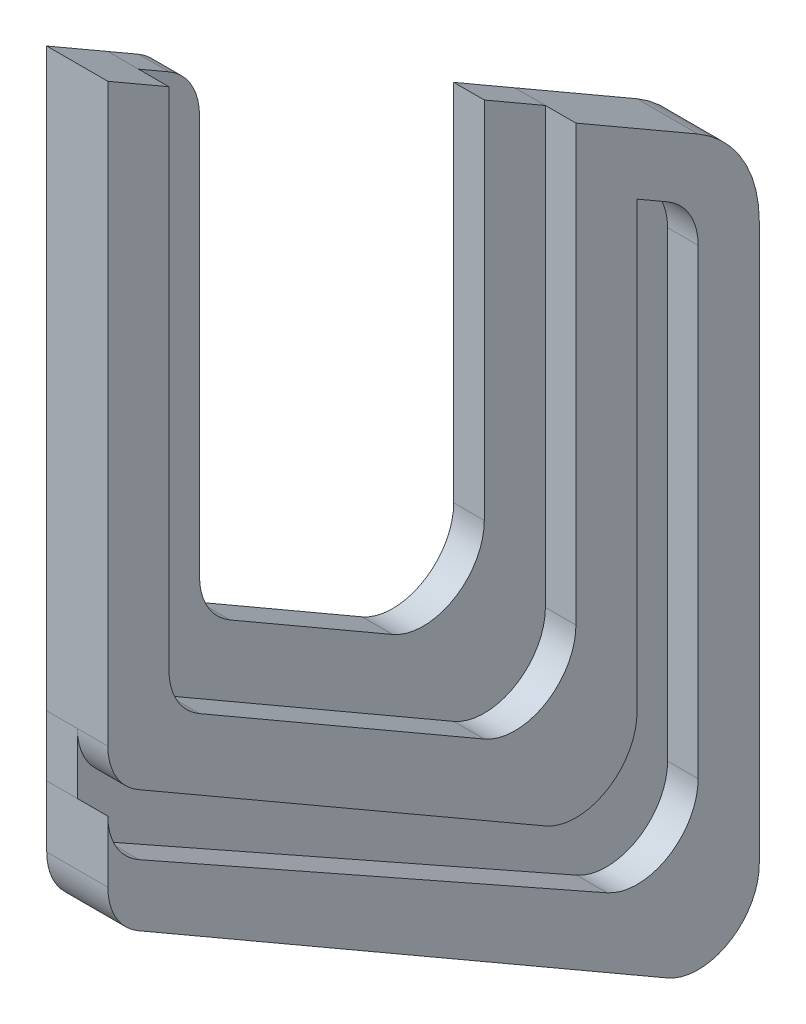
SolidWorks part; units mm, degrees
ref_plane "Plan de face" through (0, 0, 0) normal (1, 0, 0) x (0, 1, 0)
ref_plane "Plan de dessus" through (0, 0, 0) normal (0, 0, 1) x (0, 1, 0)
ref_plane "Plan de droite" through (0, 0, 0) normal (0, 1, 0) x (-1, 0, 0)
sketch "Sketch1" plane through (0, 0, 0) normal (1, 0, 0) x (0, 1, 0)
  line L0 (94.9825, 86.6025) -> (0.756, 86.6025)
  line L1 (-7.9042, 81.6025) -> (-46.3572, 15)
  line L2 (-37.697, 0) -> (34.9825, 0)
  line L3 (83.4355, 76.6025) -> (6.5295, 76.6025)
  line L4 (-2.1307, 71.6025) -> (-29.0367, 25)
  line L5 (-20.3765, 10) -> (50.756, 10)
  line L6 (94.9825, 86.6025) -> (92.0958, 81.6025)
  line L7 (-37.697, 10) -> (44.9825, 10) construction
  line L8 (50.756, 10) -> (44.9825, 0)
  line L9 (94.9825, 76.6025) -> (0.756, 76.6025) construction
  line L10 (0.756, 76.6025) -> (-37.697, 10) construction
  line L11 (50.756, 10) -> (39.209, -10)
  line L12 (-5.0175, 86.6025) -> (-9.1631, 86.6025) construction
  line L13 (-15.0175, 86.6025) -> (-19.244, 86.6025)
  line L14 (-27.9042, 81.6025) -> (-77.9042, -5)
  line L15 (-69.244, -20) -> (21.8885, -20)
  line L16 (23.4355, -10) -> (-52.1628, -10)
  line L17 (-60.8829, 4.8949) -> (-17.8831, 81.4974)
  line L18 (34.9825, 0) -> (32.0958, -5)
  line L19 (-37.697, 0) -> (44.9825, 0) construction
  line L20 (-15.0175, 86.6025) -> (-9.1631, 86.6025)
  line L21 (83.4355, 76.6025) -> (89.209, 76.6025)
  line L22 (89.209, 76.6025) -> (92.0958, 81.6025)
  arc A0 (-37.697, 0) -> (-46.3572, 15) centre (-37.697, 10) cw
  arc A1 (0.756, 86.6025) -> (-7.9042, 81.6025) centre (0.756, 76.6025) ccw
  arc A5 (-20.3765, 10) -> (-29.0367, 25) centre (-20.3765, 20) cw
  arc A6 (-37.697, 10) -> (-37.697, 10) centre (-37.697, 10) cw construction
  arc A7 (-2.1307, 71.6025) -> (6.5295, 76.6025) centre (6.5295, 66.6025) cw
  arc A8 (0.756, 76.6025) -> (0.756, 76.6025) centre (0.756, 76.6025) ccw construction
  arc A9 (-69.244, -20) -> (-77.9042, -5) centre (-69.244, -10) cw
  arc A10 (32.0958, -5) -> (23.4355, -10) centre (23.4355, 0) cw
  arc A11 (39.209, -10) -> (21.8885, -20) centre (21.8885, 0) cw
  arc A12 (-60.8829, 4.8949) -> (-52.1628, -10) centre (-52.1628, 0) ccw
  arc A13 (-27.9042, 81.6025) -> (-19.244, 86.6025) centre (-19.244, 76.6025) cw
  arc A14 (-17.8831, 81.4974) -> (-9.1631, 86.6025) centre (-9.1631, 76.6025) cw
  point P7 (-55.0175, 0)
  point P10 (-5.0175, 86.6025)
  point P44 (33.4355, -20)
  point P50 (-25.0175, 86.6025)
  dimension "D5" = 10
  dimension "D8" = 10
  dimension "D11" = 10
  dimension "D12" = 10
  dimension "D13" = 20
  dimension "D14" = 10
  dimension "D15" = 10
  dimension "D16" = 10
  dimension "D1" = 100
  dimension "D2" = 60
  dimension "D3" = 100
  dimension "D4" = 100
  dimension "D9" = 10
  dimension "D10" = 10
  dimension "10" = 20
  dimension "D6" = 10
extrude "Boss-Extrude1" add sketch "Sketch1" along normal blind 10 contours L11 A11 L15 A9 L14 A13 L13 L20 A14 L17 A12 L16 A10 L18 L2 A0 L1 A1 L0 L6 L22 L21 L3 A7 L4 A5 L5
sketch "Sketch2" plane through (10, 0, 0) normal (1, 0, 0) x (0, 1, 0)
  line L0 (-9.1631, 86.6025) -> (0.756, 86.6025)
  line L14 (-9.1631, 86.6025) -> (-19.244, 86.6025)
  line L15 (-27.9042, 81.6025) -> (-77.9042, -5)
  line L16 (-69.244, -20) -> (21.8885, -20)
  line L17 (39.209, -10) -> (50.756, 10)
  line L18 (50.756, 10) -> (-20.3765, 10)
  line L19 (-29.0367, 25) -> (-2.1307, 71.6025)
  line L20 (6.5295, 76.6025) -> (89.209, 76.6025)
  line L21 (89.209, 76.6025) -> (94.9825, 86.6025)
  line L22 (94.9825, 86.6025) -> (0.756, 86.6025)
  line L23 (-7.9042, 81.6025) -> (-46.3572, 15)
  line L24 (-37.697, 0) -> (34.9825, 0)
  line L25 (34.9825, 0) -> (32.0958, -5)
  line L26 (23.4355, -10) -> (-52.1628, -10)
  line L27 (-60.8829, 4.8949) -> (-17.8831, 81.4974)
  line L28 (-9.1631, 86.6025) -> (-19.244, 86.6025)
  line L29 (-27.9042, 81.6025) -> (-77.9042, -5)
  line L30 (-69.244, -20) -> (21.8885, -20)
  line L31 (39.209, -10) -> (50.756, 10)
  line L32 (50.756, 10) -> (-20.3765, 10)
  line L33 (-29.0367, 25) -> (-2.1307, 71.6025)
  line L34 (6.5295, 76.6025) -> (89.209, 76.6025)
  line L35 (89.209, 76.6025) -> (94.9825, 86.6025)
  line L36 (94.9825, 86.6025) -> (0.756, 86.6025)
  line L37 (-7.9042, 81.6025) -> (-46.3572, 15)
  line L38 (-37.697, 0) -> (34.9825, 0)
  line L39 (34.9825, 0) -> (32.0958, -5)
  line L40 (23.4355, -10) -> (-52.1628, -10)
  line L41 (-60.8829, 4.8949) -> (-17.8831, 81.4974)
  arc A12 (-9.1631, 86.6025) -> (-17.8831, 81.4974) centre (-9.1631, 76.6025) ccw
  arc A14 (-19.244, 86.6025) -> (-27.9042, 81.6025) centre (-19.244, 76.6025) ccw
  arc A15 (-77.9042, -5) -> (-69.244, -20) centre (-69.244, -10) ccw
  arc A16 (21.8885, -20) -> (39.209, -10) centre (21.8885, 0) ccw
  arc A17 (-29.0367, 25) -> (-20.3765, 10) centre (-20.3765, 20) ccw
  arc A18 (6.5295, 76.6025) -> (-2.1307, 71.6025) centre (6.5295, 66.6025) ccw
  arc A20 (0.756, 86.6025) -> (-7.9042, 81.6025) centre (0.756, 76.6025) ccw
  arc A21 (-46.3572, 15) -> (-37.697, 0) centre (-37.697, 10) ccw
  arc A22 (23.4355, -10) -> (32.0958, -5) centre (23.4355, 0) ccw
  arc A23 (-60.8829, 4.8949) -> (-52.1628, -10) centre (-52.1628, 0) ccw
  arc A24 (-9.1631, 86.6025) -> (-17.8831, 81.4974) centre (-9.1631, 76.6025) ccw
  arc A26 (-19.244, 86.6025) -> (-27.9042, 81.6025) centre (-19.244, 76.6025) ccw
  arc A27 (-77.9042, -5) -> (-69.244, -20) centre (-69.244, -10) ccw
  arc A28 (21.8885, -20) -> (39.209, -10) centre (21.8885, 0) ccw
  arc A29 (-29.0367, 25) -> (-20.3765, 10) centre (-20.3765, 20) ccw
  arc A30 (6.5295, 76.6025) -> (-2.1307, 71.6025) centre (6.5295, 66.6025) ccw
  arc A32 (0.756, 86.6025) -> (-7.9042, 81.6025) centre (0.756, 76.6025) ccw
  arc A33 (-46.3572, 15) -> (-37.697, 0) centre (-37.697, 10) ccw
  arc A34 (23.4355, -10) -> (32.0958, -5) centre (23.4355, 0) ccw
  arc A35 (-60.8829, 4.8949) -> (-52.1628, -10) centre (-52.1628, 0) ccw
  arc M27 (-17.8831, 81.4974) -> (-9.1631, 86.6025) centre (-9.1631, 76.6025) cw
  arc M44 (0.756, 86.6025) -> (-7.9042, 81.6025) centre (0.756, 76.6025) ccw
  line M45 (-7.9042, 81.6025) -> (-46.3572, 15)
  arc M46 (-46.3572, 15) -> (-37.697, 0) centre (-37.697, 10) ccw
  line M47 (-37.697, 0) -> (34.9825, 0)
  line M48 (34.9825, 0) -> (32.0958, -5)
  arc M49 (32.0958, -5) -> (23.4355, -10) centre (23.4355, 0) cw
  line M50 (23.4355, -10) -> (-52.1628, -10)
  arc M51 (-52.1628, -10) -> (-60.8829, 4.8949) centre (-52.1628, 0) cw
  line M52 (-60.8829, 4.8949) -> (-17.8831, 81.4974)
  dimension "D1" = 0
extrude "Boss-Extrude2" add sketch "Sketch2" against normal blind 5 from offset 5 separate body contours L0 M27 M52 M51 M50 M49 M48 M47 M46 M45 M44 offset against normal yes
sketch "Sketch3" plane through (5, 0, 0) normal (1, 0, 0) x (0, 1, 0)
  line L14 (50.756, 10) -> (-20.3765, 10)
  line L15 (-29.0367, 25) -> (-2.1307, 71.6025)
  line L16 (6.5295, 76.6025) -> (89.209, 76.6025)
  line L17 (89.209, 76.6025) -> (94.9825, 86.6025)
  line L18 (94.9825, 86.6025) -> (0.756, 86.6025)
  line L19 (-7.9042, 81.6025) -> (-46.3572, 15)
  line L20 (-37.697, 0) -> (34.9825, 0)
  line L21 (34.9825, 0) -> (32.0958, -5)
  line L22 (23.4355, -10) -> (-52.1628, -10)
  line L23 (-60.8829, 4.8949) -> (-17.8831, 81.4974)
  line L24 (-9.1631, 86.6025) -> (-19.244, 86.6025)
  line L25 (-27.9042, 81.6025) -> (-77.9042, -5)
  line L26 (-69.244, -20) -> (21.8885, -20)
  line L27 (39.209, -10) -> (50.756, 10)
  line L28 (50.756, 10) -> (-20.3765, 10)
  line L29 (-29.0367, 25) -> (-2.1307, 71.6025)
  line L30 (6.5295, 76.6025) -> (89.209, 76.6025)
  line L31 (89.209, 76.6025) -> (94.9825, 86.6025)
  line L32 (94.9825, 86.6025) -> (0.756, 86.6025)
  line L33 (-7.9042, 81.6025) -> (-46.3572, 15)
  line L34 (-37.697, 0) -> (34.9825, 0)
  line L35 (34.9825, 0) -> (32.0958, -5)
  line L36 (23.4355, -10) -> (-52.1628, -10)
  line L37 (-60.8829, 4.8949) -> (-17.8831, 81.4974)
  line L38 (-9.1631, 86.6025) -> (-19.244, 86.6025)
  line L39 (-27.9042, 81.6025) -> (-77.9042, -5)
  line L40 (-69.244, -20) -> (21.8885, -20)
  line L41 (39.209, -10) -> (50.756, 10)
  line L42 (-11.7162, 35) -> (3.6428, 61.6025)
  line L43 (12.303, 66.6025) -> (77.662, 66.6025)
  line L44 (56.5295, 20) -> (-3.0559, 20)
  line L45 (89.209, 76.6025) -> (86.3223, 71.6025)
  line L46 (50.756, 20) -> (-20.3765, 20) construction
  line L47 (6.5295, 66.6025) -> (89.209, 66.6025) construction
  line L48 (56.5295, 20) -> (50.756, 10)
  line L49 (-20.3765, 20) -> (6.5295, 66.6025) construction
  arc A10 (-29.0367, 25) -> (-20.3765, 10) centre (-20.3765, 20) ccw
  arc A11 (6.5295, 76.6025) -> (-2.1307, 71.6025) centre (6.5295, 66.6025) ccw
  arc A12 (0.756, 86.6025) -> (-7.9042, 81.6025) centre (0.756, 76.6025) ccw
  arc A13 (-46.3572, 15) -> (-37.697, 0) centre (-37.697, 10) ccw
  arc A14 (23.4355, -10) -> (32.0958, -5) centre (23.4355, 0) ccw
  arc A15 (-60.8829, 4.8949) -> (-52.1628, -10) centre (-52.1628, 0) ccw
  arc A16 (-9.1631, 86.6025) -> (-17.8831, 81.4974) centre (-9.1631, 76.6025) ccw
  arc A17 (-19.244, 86.6025) -> (-27.9042, 81.6025) centre (-19.244, 76.6025) ccw
  arc A18 (-77.9042, -5) -> (-69.244, -20) centre (-69.244, -10) ccw
  arc A19 (21.8885, -20) -> (39.209, -10) centre (21.8885, 0) ccw
  arc A20 (-29.0367, 25) -> (-20.3765, 10) centre (-20.3765, 20) ccw
  arc A21 (6.5295, 76.6025) -> (-2.1307, 71.6025) centre (6.5295, 66.6025) ccw
  arc A22 (0.756, 86.6025) -> (-7.9042, 81.6025) centre (0.756, 76.6025) ccw
  arc A23 (-46.3572, 15) -> (-37.697, 0) centre (-37.697, 10) ccw
  arc A24 (23.4355, -10) -> (32.0958, -5) centre (23.4355, 0) ccw
  arc A25 (-60.8829, 4.8949) -> (-52.1628, -10) centre (-52.1628, 0) ccw
  arc A26 (-9.1631, 86.6025) -> (-17.8831, 81.4974) centre (-9.1631, 76.6025) ccw
  arc A27 (-19.244, 86.6025) -> (-27.9042, 81.6025) centre (-19.244, 76.6025) ccw
  arc A28 (-77.9042, -5) -> (-69.244, -20) centre (-69.244, -10) ccw
  arc A29 (21.8885, -20) -> (39.209, -10) centre (21.8885, 0) ccw
  arc A30 (86.3223, 71.6025) -> (77.662, 66.6025) centre (77.662, 76.6025) cw
  arc A31 (-11.7162, 35) -> (-3.0559, 20) centre (-3.0559, 30) ccw
  arc A32 (3.6428, 61.6025) -> (12.303, 66.6025) centre (12.303, 56.6025) cw
  arc A33 (6.5295, 66.6025) -> (6.5295, 66.6025) centre (6.5295, 66.6025) ccw construction
  dimension "D3" = 10
  dimension "D4" = 10
  dimension "D1" = 0
  dimension "D2" = 10
extrude "Boss-Extrude3" add sketch "Sketch3" against normal blind 5 separate body contours L42 A32 L43 A30 L45 L30 A21 L29 A20 L28 L48 L44 A31
